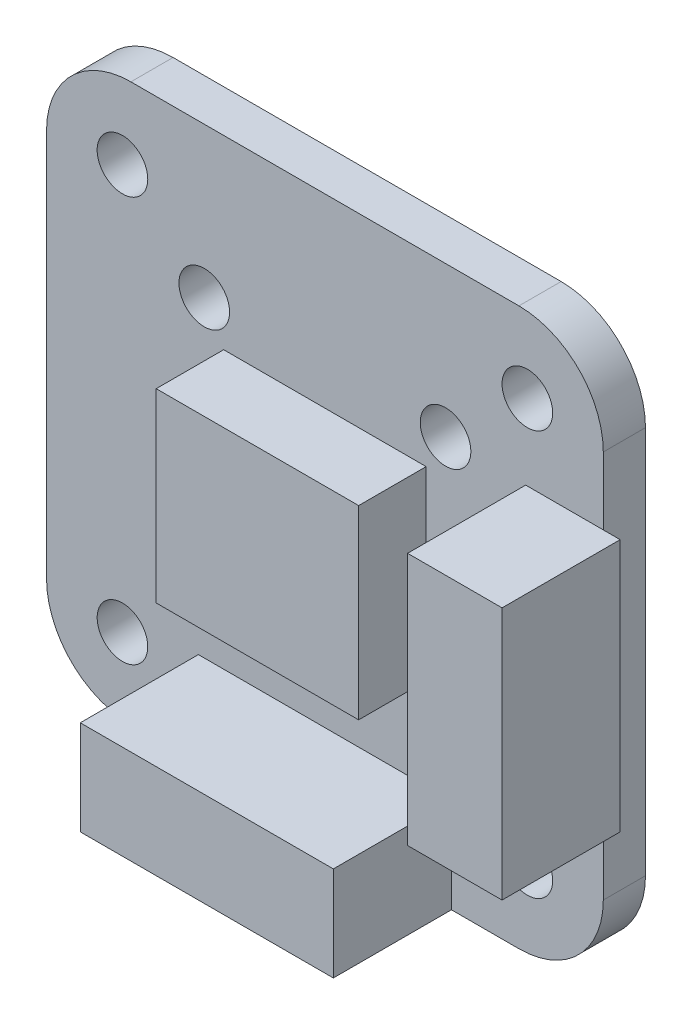
SolidWorks part; units mm, degrees
ref_plane "Front Plane" through (0, 0, 0) normal (0, 0, 1) x (1, 0, 0)
ref_plane "Top Plane" through (0, 0, 0) normal (0, 1, 0) x (1, 0, 0)
ref_plane "Right Plane" through (0, 0, 0) normal (1, 0, 0) x (0, 0, -1)
sketch "Sketch1" plane through (0, 0, 0) normal (0, 0, 1) x (1, 0, 0)
  line L0 (-3.4418, 11.1595) -> (-3.4418, -21.8405) construction
  line L1 (-19.9418, 11.1595) -> (13.0582, 11.1595)
  line L2 (-19.9418, 11.1595) -> (-19.9418, -21.8405)
  line L3 (-19.9418, -21.8405) -> (13.0582, -21.8405)
  line L4 (13.0582, 11.1595) -> (13.0582, -21.8405)
  line L21 (-19.9418, -5.3405) -> (12.9985, -5.3405) construction
  circle A0 centre (-15.4418, 6.6595) radius 1.5
  circle A1 centre (8.5582, 6.6595) radius 1.5
  circle A2 centre (-15.4418, -17.3405) radius 1.5
  circle A3 centre (8.5582, -17.3405) radius 1.5
  circle A4 centre (-10.5918, -12.9405) radius 1.5
  circle A5 centre (3.7082, -12.9405) radius 1.5
  circle A6 centre (-10.5918, 2.2595) radius 1.5
  circle A7 centre (3.7082, 2.2595) radius 1.5
  dimension "D11" = 3
  dimension "D12" = 4.5
  dimension "D14" = 3
  dimension "D15" = 9.35
  dimension "D16" = 8.9
  dimension "D1" = 33
  dimension "D2" = 33
  dimension "D13" = 4.5
extrude "Boss-Extrude1" add sketch "Sketch1" along normal blind 2.5
fillet "Fillet1" radius 5 4 edges at (13.0582, -21.8405, 1.25) (-19.9418, -21.8405, 1.25) (-19.9418, 11.1595, 1.25) (13.0582, 11.1595, 1.25)
sketch "Sketch2" plane through (0, 0, 2.5) normal (0, 0, 1) x (1, 0, 0)
  line L0 (-3.4418, 11.1595) -> (-3.4418, -21.8405) construction
  line L1 (-10.9418, -16.2405) -> (4.0582, -16.2405)
  line L2 (-10.9418, -16.2405) -> (-10.9418, -21.8405)
  line L3 (-10.9418, -21.8405) -> (4.0582, -21.8405)
  line L4 (4.0582, -16.2405) -> (4.0582, -21.8405)
  line L5 (-19.9418, -21.8405) -> (13.0582, -21.8405) construction
  line L6 (-19.9418, -5.3405) -> (12.9985, -5.3405) construction
  line L7 (8.4582, 2.1595) -> (14.0582, 2.1595)
  line L8 (8.4582, 2.1595) -> (8.4582, -12.8405)
  line L9 (8.4582, -12.8405) -> (14.0582, -12.8405)
  line L10 (14.0582, 2.1595) -> (14.0582, -12.8405)
  line L11 (13.0582, 11.1595) -> (13.0582, -21.8405) construction
  point P4 (-3.4418, -16.2405)
  point P13 (8.4582, -5.3405)
  dimension "D1" = 15
  dimension "D2" = 5.6
  dimension "D3" = 15
  dimension "D4" = 5.6
  dimension "D5" = 1
extrude "Boss-Extrude2" add sketch "Sketch2" along normal blind 7
sketch "Sketch3" plane through (0, 0, 2.5) normal (0, 0, 1) x (1, 0, 0)
  line L0 (-19.9418, -5.3405) -> (12.9985, -5.3405) construction
  line L1 (-9.4418, 0.1595) -> (2.5582, 0.1595)
  line L2 (-9.4418, 0.1595) -> (-9.4418, -10.8405)
  line L3 (-9.4418, -10.8405) -> (2.5582, -10.8405)
  line L4 (2.5582, 0.1595) -> (2.5582, -10.8405)
  line L5 (-3.4418, 11.1595) -> (-3.4418, -21.8405) construction
  point P4 (-9.4418, -5.3405)
  point P7 (-3.4418, 0.1595)
  dimension "D1" = 12
  dimension "D2" = 11
extrude "Boss-Extrude3" add sketch "Sketch3" along normal blind 4
